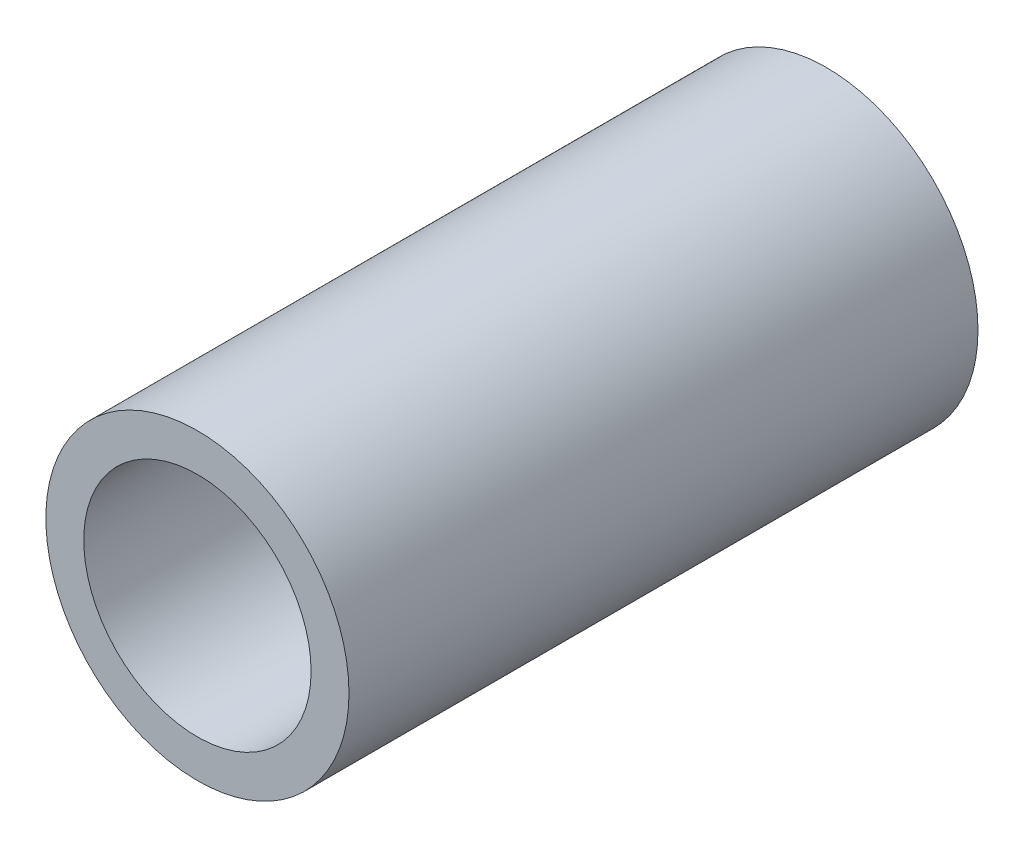
SolidWorks part; units mm, degrees
ref_plane "Alzado" through (0, 0, 0) normal (0, 0, 1) x (1, 0, 0)
ref_plane "Planta" through (0, 0, 0) normal (0, 1, 0) x (1, 0, 0)
ref_plane "Vista lateral" through (0, 0, 0) normal (1, 0, 0) x (0, 0, -1)
sketch "Croquis1" plane through (0, 0, 0) normal (0, 0, 1) x (1, 0, 0)
  line L0 (0, -55) -> (0, 55) construction
  circle A0 centre (0, 0) radius 20
  circle A1 centre (0, 0) radius 15
  dimension "D1" = 40
  dimension "D2" = 30
extrude "Saliente-Extruir1" add sketch "Croquis1" along normal blind 83
